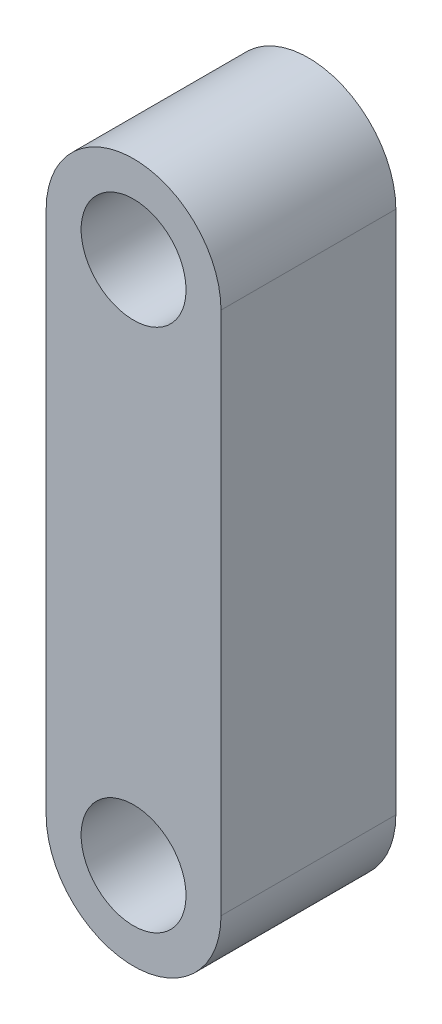
SolidWorks part; units mm, degrees
ref_plane "Plan de face" through (0, 0, 0) normal (0, 0, 1) x (1, 0, 0)
ref_plane "Plan de dessus" through (0, 0, 0) normal (0, 1, 0) x (1, 0, 0)
ref_plane "Plan de droite" through (0, 0, 0) normal (1, 0, 0) x (0, 0, -1)
sketch "Sketch1" plane through (0, 0, 0) normal (0, 0, 1) x (1, 0, 0)
  line L0 (-2.5, 0) -> (2.5, 0)
  line L1 (-2.5, 0) -> (-2.5, 15)
  line L2 (2.5, 0) -> (2.5, 15)
  line L3 (-2.5, 15) -> (2.5, 15)
  circle A0 centre (0, 0) radius 1.5
  circle A1 centre (0, 0) radius 2.5
  circle A2 centre (0, 15) radius 2.5
  circle A3 centre (0, 15) radius 1.5
  dimension "D1" = 3
  dimension "D2" = 5
  dimension "D4" = 3
  dimension "D3" = 15
extrude "Boss-Extrude1" add sketch "Sketch1" along normal blind 5 contours A3 L3 A2 | A3 L3 A2 | A2 L1 A1 L2 | L0 A1 A0 | L0 A1 A0
